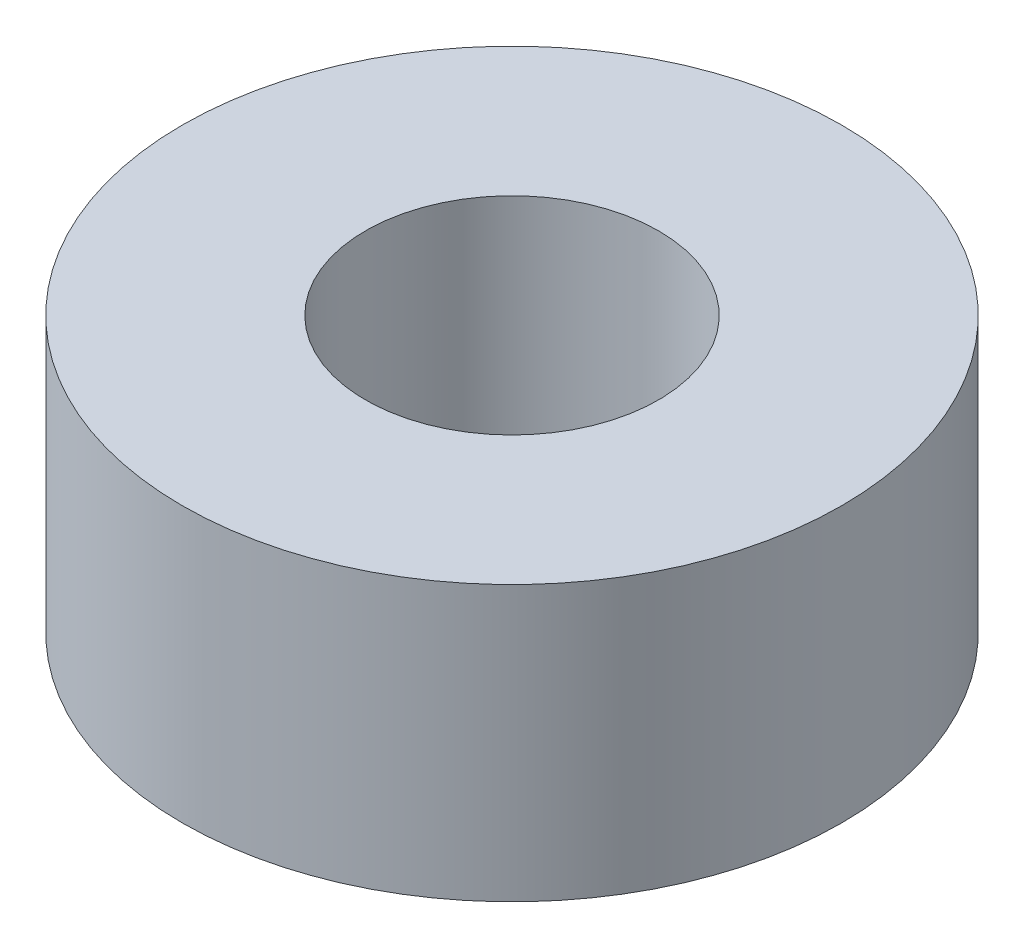
SolidWorks part; units mm, degrees
ref_plane "Płaszczyzna przednia" through (0, 0, 0) normal (0, 0, 1) x (1, 0, 0)
ref_plane "Płaszczyzna górna" through (0, 0, 0) normal (0, 1, 0) x (1, 0, 0)
ref_plane "Płaszczyzna prawa" through (0, 0, 0) normal (1, 0, 0) x (0, 0, -1)
sketch "Szkic2" plane through (0, 0, 0) normal (0, 0, 1) x (1, 0, 0)
  line L0 (0, 0) -> (0, 5.6562) construction
  line L1 (1.6, 0) -> (3.6, 0)
  line L2 (1.6, 0) -> (1.6, 3)
  line L3 (1.6, 3) -> (3.6, 3)
  line L4 (3.6, 0) -> (3.6, 3)
  dimension "D1" = 3.2
  dimension "D2" = 3
  dimension "D3" = 2
revolve "Obrót1" add sketch "Szkic2" angle 360 about L0
